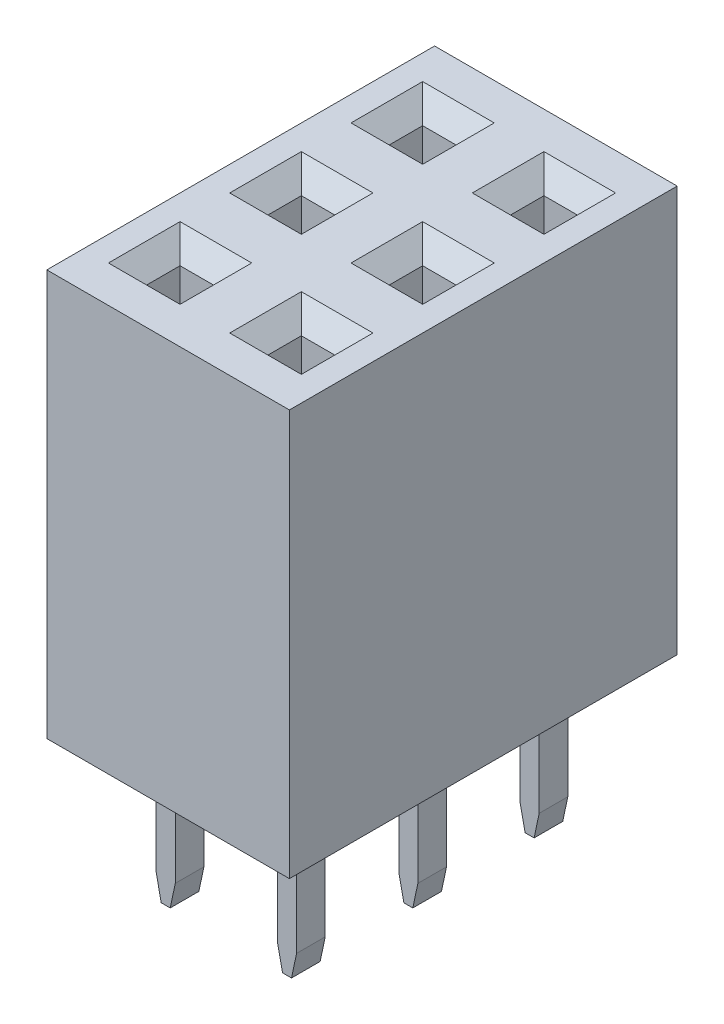
SolidWorks part; units mm, degrees
ref_plane "Спереди" through (0, 0, 0) normal (0, 0, 1) x (1, 0, 0)
ref_plane "Сверху" through (0, 0, 0) normal (0, 1, 0) x (1, 0, 0)
ref_plane "Справа" through (0, 0, 0) normal (1, 0, 0) x (0, 0, -1)
ref_plane "Плоскость1" through (0, 0, 0) normal (0, 1, 0) x (-1, 0, 0)
sketch "Эскиз1" plane through (0, 0, 0) normal (0, 1, 0) x (-1, 0, 0)
  line L0 (0, 0) -> (-5.5295, 0) construction
  line L1 (0, 0) -> (0, -2.1715) construction
  line L2 (-1.27, 1.52) -> (1.27, 1.52)
  line L3 (-1.27, 1.52) -> (-1.27, -1.52)
  line L4 (-1.27, -1.52) -> (1.27, -1.52) construction
  line L5 (1.27, 1.52) -> (1.27, -1.52) construction
  line L6 (1.27, 1.52) -> (3.81, 1.52)
  line L7 (-1.27, -1.52) -> (-1.27, -6.6)
  line L8 (-1.27, -6.6) -> (3.81, -6.6)
  line L9 (1.27, -1.52) -> (1.27, -5.2331) construction
  line L10 (3.81, 1.52) -> (3.81, -1.52)
  line L11 (3.81, -1.52) -> (3.81, -6.6)
  point P0 (-1.27, 1.52)
  point P1 (1.27, -1.52)
  point P2 (-1.27, -1.52)
  point P3 (1.27, 1.52)
  dimension "D1" = 2.54
  dimension "D2" = 8.12
  dimension "D6" = 1.52
extrude "Бобышка-Вытянуть1" add sketch "Эскиз1" along normal blind 8.5
sketch "Эскиз4" plane through (0, 8.5, 0) normal (0, 1, 0) x (1, 0, 0)
  line L0 (0, 0) -> (0.806, 0) construction
  line L1 (0, 0) -> (0, 1.2961) construction
  line L3 (-0.35, 0.35) -> (0.35, 0.35)
  line L4 (-0.35, 0.35) -> (-0.35, -0.35)
  line L5 (-0.35, -0.35) -> (0.35, -0.35)
  line L6 (0.35, 0.35) -> (0.35, -0.35)
  dimension "D1" = 0.7
extrude "Вырез-Вытянуть1" cut sketch "Эскиз4" against normal blind 8.2
chamfer "Фаска3" distance 0.4 angle 45 4 edges at (0.35, 8.5, 0) (0, 8.5, -0.35) (0, 8.5, 0.35) (-0.35, 8.5, 0)
sketch "Эскиз2" plane through (0, 0, 0) normal (0, 1, 0) x (-1, 0, 0)
  line L0 (0, 0) -> (0, -0.4454) construction
  line L1 (0.2, 0.3) -> (-0.2, 0.3)
  line L2 (0.2, 0.3) -> (0.2, -0.3)
  line L3 (0.2, -0.3) -> (-0.2, -0.3)
  line L4 (-0.2, 0.3) -> (-0.2, -0.3)
  line L5 (0, 0) -> (-0.4704, 0) construction
  dimension "D1" = 0.6
  dimension "D2" = 0.4
extrude "Бобышка-Вытянуть2" add sketch "Эскиз2" against normal blind 3
chamfer "Фаска2" distance 0.5 angle 12 2 edges at (0.2, -3, 0) (-0.2, -3, 0)
pattern_linear "Линейный массив1" count 3 spacing 2.54 along (0, 0, -1) count 2 spacing 2.54 along (-1, 0, 0) of "Вырез-Вытянуть1", "Фаска3", "Бобышка-Вытянуть2", "Фаска2"
